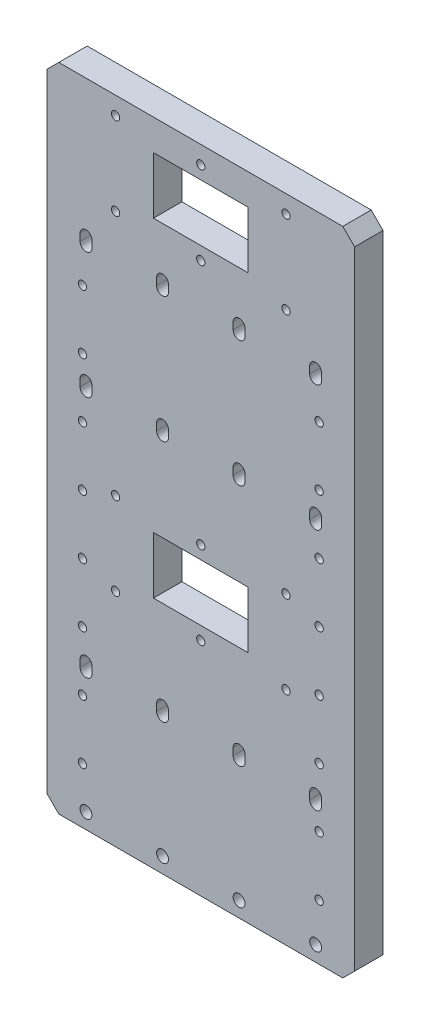
SolidWorks part; units mm, degrees
material "Beech"
ref_plane "Front Plane" through (0, 0, 0) normal (0, 0, 1) x (1, 0, 0)
ref_plane "Top Plane" through (0, 0, 0) normal (0, 1, 0) x (1, 0, 0)
ref_plane "Right Plane" through (0, 0, 0) normal (1, 0, 0) x (0, 0, -1)
sketch "Model" plane through (0, 0, 0) normal (0, 0, 1) x (1, 0, 0)
  line L0 (5, 275) -> (0, 270)
  line L1 (125, 275) -> (5, 275)
  line L2 (130, 270) -> (125, 275)
  line L3 (125, 0) -> (130, 5)
  line L4 (0, 5) -> (5, 0)
  line L5 (85, 99) -> (45, 99)
  line L6 (85, 123) -> (85, 99)
  line L7 (45, 123) -> (85, 123)
  line L8 (45, 99) -> (45, 123)
  line L9 (13.99, 163.82) -> (13.99, 160.82)
  line L10 (18.99, 160.82) -> (18.99, 163.82)
  line L11 (46.33, 163.82) -> (46.33, 160.82)
  line L12 (51.33, 160.82) -> (51.33, 163.82)
  line L13 (78.67, 163.82) -> (78.67, 160.82)
  line L14 (83.67, 160.82) -> (83.67, 163.82)
  line L15 (111.01, 163.82) -> (111.01, 160.82)
  line L16 (116.01, 160.82) -> (116.01, 163.82)
  line L17 (13.99, 217) -> (13.99, 214)
  line L18 (18.99, 214) -> (18.99, 217)
  line L19 (51.33, 214) -> (51.33, 217)
  line L20 (46.33, 217) -> (46.33, 214)
  line L21 (83.67, 214) -> (83.67, 217)
  line L22 (78.67, 217) -> (78.67, 214)
  line L23 (116.01, 214) -> (116.01, 217)
  line L24 (111.01, 217) -> (111.01, 214)
  line L25 (18.99, 58.18) -> (18.99, 61.18)
  line L26 (13.99, 61.18) -> (13.99, 58.18)
  line L27 (51.33, 58.18) -> (51.33, 61.18)
  line L28 (46.33, 61.18) -> (46.33, 58.18)
  line L29 (83.67, 58.18) -> (83.67, 61.18)
  line L30 (78.67, 61.18) -> (78.67, 58.18)
  line L31 (116.01, 58.18) -> (116.01, 61.18)
  line L32 (111.01, 61.18) -> (111.01, 58.18)
  line L33 (85, 262) -> (45, 262)
  line L34 (45, 262) -> (45, 238)
  line L35 (45, 238) -> (85, 238)
  line L36 (85, 238) -> (85, 262)
  line L37 (0, 270) -> (0, 5)
  line L38 (130, 5) -> (130, 270)
  line L39 (5, 0) -> (125, 0)
  line L40 (16.49, 6.5) -> (113.51, 6.5) construction
  line L41 (113.51, 6.5) -> (113.51, 61.18) construction
  line L42 (113.51, 61.18) -> (16.49, 61.18) construction
  line L43 (16.49, 61.18) -> (16.49, 6.5) construction
  line L44 (48.83, 61.18) -> (48.83, 6.5) construction
  line L45 (81.17, 61.18) -> (81.17, 6.5) construction
  line L46 (16.49, 58.18) -> (113.51, 58.18) construction
  line L47 (16.49, 163.82) -> (113.51, 163.82) construction
  line L48 (15, 48.5) -> (115, 48.5) construction
  line L49 (15, 48.5) -> (15, 23.5) construction
  line L50 (15, 23.5) -> (115, 23.5) construction
  line L51 (115, 48.5) -> (115, 23.5) construction
  line L52 (15, 73.5) -> (115, 73.5) construction
  line L53 (15, 73.5) -> (15, 48.5) construction
  line L54 (15, 48.5) -> (115, 48.5) construction
  line L55 (115, 73.5) -> (115, 48.5) construction
  line L56 (15, 98.5) -> (115, 98.5) construction
  line L57 (15, 98.5) -> (15, 73.5) construction
  line L58 (15, 73.5) -> (115, 73.5) construction
  line L59 (115, 98.5) -> (115, 73.5) construction
  line L60 (15, 123.5) -> (115, 123.5) construction
  line L61 (15, 123.5) -> (15, 98.5) construction
  line L62 (15, 98.5) -> (115, 98.5) construction
  line L63 (115, 123.5) -> (115, 98.5) construction
  line L64 (15, 148.5) -> (115, 148.5) construction
  line L65 (15, 148.5) -> (15, 123.5) construction
  line L66 (15, 123.5) -> (115, 123.5) construction
  line L67 (115, 148.5) -> (115, 123.5) construction
  line L68 (15, 173.5) -> (115, 173.5) construction
  line L69 (15, 173.5) -> (15, 148.5) construction
  line L70 (15, 148.5) -> (115, 148.5) construction
  line L71 (115, 173.5) -> (115, 148.5) construction
  line L72 (15, 198.5) -> (115, 198.5) construction
  line L73 (15, 198.5) -> (15, 173.5) construction
  line L74 (15, 173.5) -> (115, 173.5) construction
  line L75 (115, 198.5) -> (115, 173.5) construction
  line L76 (29, 232.5) -> (101, 232.5) construction
  line L77 (29, 232.5) -> (29, 267.5) construction
  line L78 (29, 267.5) -> (101, 267.5) construction
  line L79 (101, 232.5) -> (101, 267.5) construction
  line L80 (29, 93.5) -> (101, 93.5) construction
  line L81 (29, 93.5) -> (29, 128.5) construction
  line L82 (29, 128.5) -> (101, 128.5) construction
  line L83 (101, 93.5) -> (101, 128.5) construction
  line L84 (113.51, 163.82) -> (113.51, 61.18) construction
  line L85 (16.49, 217) -> (16.49, 163.82) construction
  line L86 (16.49, 163.82) -> (16.49, 61.18) construction
  line L87 (48.83, 217) -> (48.83, 163.82) construction
  line L88 (48.83, 163.82) -> (48.83, 61.18) construction
  line L89 (81.17, 217) -> (81.17, 163.82) construction
  line L90 (81.17, 163.82) -> (81.17, 61.18) construction
  line L91 (113.51, 217) -> (113.51, 163.82) construction
  line L92 (16.49, 217) -> (113.51, 217) construction
  line L93 (16.49, 214) -> (113.51, 214) construction
  line L94 (16.49, 160.82) -> (113.51, 160.82) construction
  line L95 (0, 5) -> (0, 0) construction
  line L96 (5, 0) -> (0, 0) construction
  circle A0 centre (16.49, 6.5) radius 2.5
  circle A1 centre (48.83, 6.5) radius 2.5
  circle A2 centre (81.17, 6.5) radius 2.5
  circle A3 centre (113.51, 6.5) radius 2.5
  circle A4 centre (29, 128.5) radius 1.75
  circle A5 centre (65, 128.5) radius 1.75
  circle A6 centre (101, 128.5) radius 1.75
  circle A7 centre (101, 93.5) radius 1.75
  circle A8 centre (65, 93.5) radius 1.75
  circle A9 centre (29, 93.5) radius 1.75
  circle A10 centre (29, 267.5) radius 1.75
  circle A11 centre (65, 267.5) radius 1.75
  circle A12 centre (101, 267.5) radius 1.75
  circle A13 centre (101, 232.5) radius 1.75
  circle A14 centre (65, 232.5) radius 1.75
  circle A15 centre (29, 232.5) radius 1.75
  circle A16 centre (15, 198.5) radius 1.75
  circle A17 centre (15, 173.5) radius 1.75
  circle A18 centre (15, 148.5) radius 1.75
  circle A19 centre (15, 123.5) radius 1.75
  circle A20 centre (15, 98.5) radius 1.75
  circle A21 centre (15, 73.5) radius 1.75
  circle A22 centre (15, 48.5) radius 1.75
  circle A23 centre (15, 23.5) radius 1.75
  circle A24 centre (115, 23.5) radius 1.75
  circle A25 centre (115, 48.5) radius 1.75
  circle A26 centre (115, 73.5) radius 1.75
  circle A27 centre (115, 98.5) radius 1.75
  circle A28 centre (115, 123.5) radius 1.75
  circle A29 centre (115, 148.5) radius 1.75
  circle A30 centre (115, 173.5) radius 1.75
  circle A31 centre (115, 198.5) radius 1.75
  arc A32 (13.99, 160.82) -> (18.99, 160.82) centre (16.49, 160.82) ccw
  arc A33 (18.99, 163.82) -> (13.99, 163.82) centre (16.49, 163.82) ccw
  arc A34 (46.33, 160.82) -> (51.33, 160.82) centre (48.83, 160.82) ccw
  arc A35 (51.33, 163.82) -> (46.33, 163.82) centre (48.83, 163.82) ccw
  arc A36 (78.67, 160.82) -> (83.67, 160.82) centre (81.17, 160.82) ccw
  arc A37 (83.67, 163.82) -> (78.67, 163.82) centre (81.17, 163.82) ccw
  arc A38 (111.01, 160.82) -> (116.01, 160.82) centre (113.51, 160.82) ccw
  arc A39 (116.01, 163.82) -> (111.01, 163.82) centre (113.51, 163.82) ccw
  arc A40 (13.99, 214) -> (18.99, 214) centre (16.49, 214) ccw
  arc A41 (18.99, 217) -> (13.99, 217) centre (16.49, 217) ccw
  arc A42 (46.33, 214) -> (51.33, 214) centre (48.83, 214) ccw
  arc A43 (51.33, 217) -> (46.33, 217) centre (48.83, 217) ccw
  arc A44 (78.67, 214) -> (83.67, 214) centre (81.17, 214) ccw
  arc A45 (83.67, 217) -> (78.67, 217) centre (81.17, 217) ccw
  arc A46 (111.01, 214) -> (116.01, 214) centre (113.51, 214) ccw
  arc A47 (116.01, 217) -> (111.01, 217) centre (113.51, 217) ccw
  arc A48 (13.99, 58.18) -> (18.99, 58.18) centre (16.49, 58.18) ccw
  arc A49 (18.99, 61.18) -> (13.99, 61.18) centre (16.49, 61.18) ccw
  arc A50 (46.33, 58.18) -> (51.33, 58.18) centre (48.83, 58.18) ccw
  arc A51 (51.33, 61.18) -> (46.33, 61.18) centre (48.83, 61.18) ccw
  arc A52 (78.67, 58.18) -> (83.67, 58.18) centre (81.17, 58.18) ccw
  arc A53 (83.67, 61.18) -> (78.67, 61.18) centre (81.17, 61.18) ccw
  arc A54 (111.01, 58.18) -> (116.01, 58.18) centre (113.51, 58.18) ccw
  arc A55 (116.01, 61.18) -> (111.01, 61.18) centre (113.51, 61.18) ccw
  dimension "D39" = 5
  dimension "D40" = 3.5
  dimension "D1" = 275
  dimension "D2" = 130
  dimension "D3" = 99
  dimension "D4" = 24
  dimension "D5" = 115
  dimension "D6" = 6.5
  dimension "D7" = 54.68
  dimension "D8" = 23.5
  dimension "D9" = 25
  dimension "D10" = 25
  dimension "D11" = 25
  dimension "D12" = 25
  dimension "D13" = 25
  dimension "D14" = 25
  dimension "D15" = 25
  dimension "D16" = 3
  dimension "D17" = 34
  dimension "D18" = 35
  dimension "D19" = 16.49
  dimension "D20" = 15
  dimension "D21" = 32.34
  dimension "D22" = 32.34
  dimension "D23" = 32.34
  dimension "D24" = 100
  dimension "D25" = 102.64
  dimension "D26" = 35
  dimension "D27" = 5.5
  dimension "D28" = 72
  dimension "D29" = 16
  dimension "D30" = 29
  dimension "D31" = 40
  dimension "D32" = 53.18
  dimension "D33" = 5.5
  dimension "D34" = 16
  dimension "D35" = 72
  dimension "D36" = 5
  dimension "D37" = 5
  dimension "D38" = 5
extrude "Boss-Extrude1" add sketch "Model" along normal blind 12
